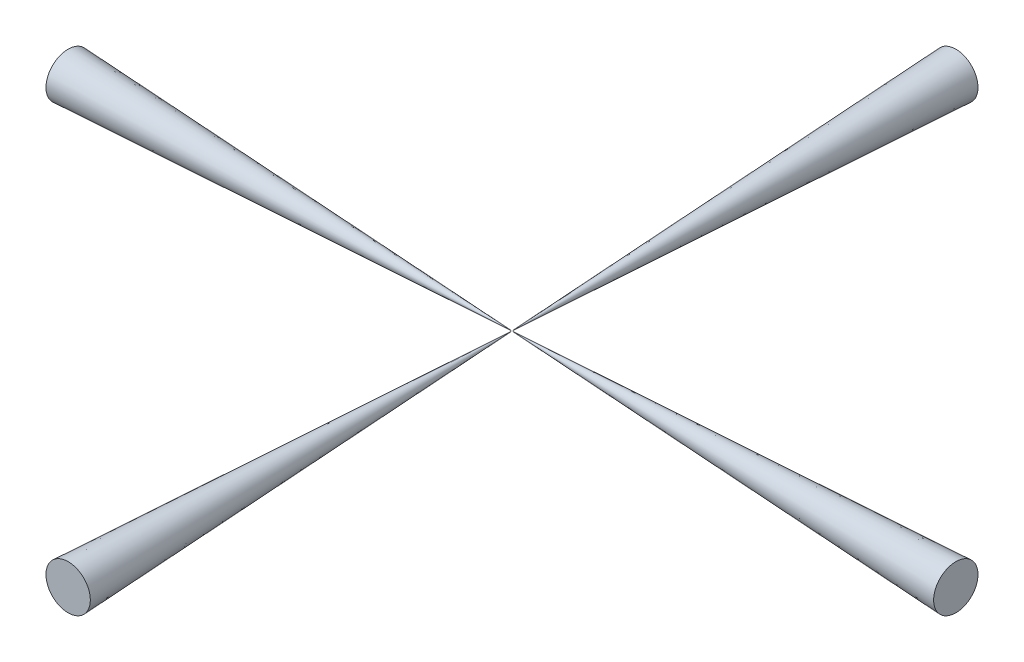
SolidWorks part; units mm, degrees
ref_plane "前视基准面" through (0, 0, 0) normal (0, 0, 1) x (1, 0, 0)
ref_plane "上视基准面" through (0, 0, 0) normal (0, 1, 0) x (1, 0, 0)
ref_plane "右视基准面" through (0, 0, 0) normal (1, 0, 0) x (0, 0, -1)
sketch "草图2" plane through (0, 0, 0) normal (0, 1, 0) x (1, 0, 0)
  line L0 (0, 0) -> (0, 0.0125)
  line L1 (0, 0.0125) -> (200, 10)
  line L2 (200, 10) -> (200, 0)
  line L3 (200, 0) -> (0, 0)
  dimension "D1" = 0.0125
  dimension "D2" = 10
  dimension "D3" = 200
revolve "旋转5" add sketch "草图2" angle 360 about L3
mirror "镜向1" of "旋转5"
sketch "草图5" plane through (0, 0, 0) normal (0, 0, 1) x (1, 0, 0)
  line L0 (0, 1.1124) -> (0, -1.4366) construction
pattern_circular "阵列(圆周)3" count 2 every 90 about axis through (0, 1.1124, 0) along (0, -1, 0) of bodies 107
sketch "草图6" plane through (0, 0, 0) normal (0, 1, 0) x (1, 0, 0)
  line L0 (0.3145, -0.3145) -> (-0.3145, 0.3145) construction
  line L1 (-0.0134, 0) -> (0.0136, 0) construction
  dimension "D1" = 45
